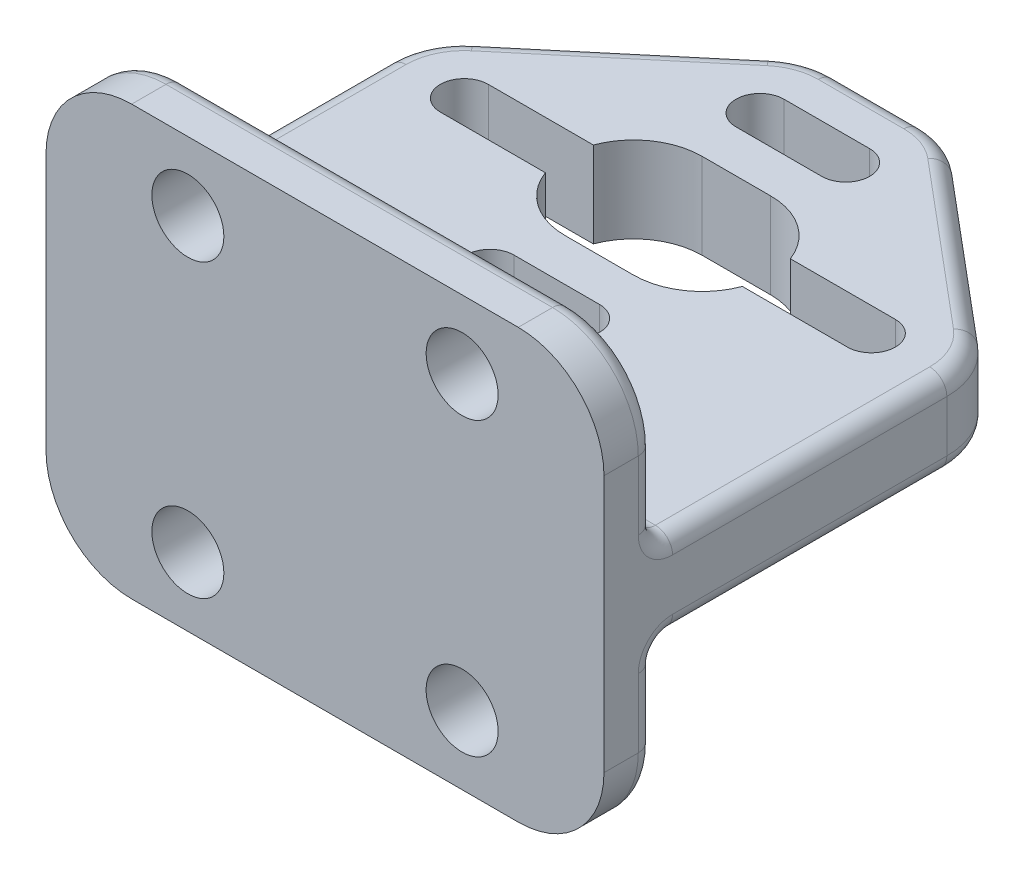
SolidWorks part; units mm, degrees
ref_plane "Front Plane" through (0, 0, 0) normal (0, 0, 1) x (1, 0, 0)
ref_plane "Top Plane" through (0, 0, 0) normal (0, 1, 0) x (1, 0, 0)
ref_plane "Right Plane" through (0, 0, 0) normal (1, 0, 0) x (0, 0, -1)
sketch "Sketch1" plane through (0, 0, 0) normal (0, 1, 0) x (1, 0, 0)
  line L0 (-9.375, 0) -> (9.375, 0) construction
  line L1 (0, -7.875) -> (0, 7.875) construction
  line L2 (-9.375, 1.4) -> (14.375, 1.4)
  line L3 (-9.375, -1.4) -> (14.375, -1.4)
  line L4 (0, 9.275) -> (5, 9.275)
  line L5 (5, 6.475) -> (0, 6.475)
  line L6 (0, -6.475) -> (5, -6.475)
  line L7 (5, -9.275) -> (0, -9.275)
  line L8 (0, 12.275) -> (5, 12.275)
  line L12 (5, -12.275) -> (0, -12.275)
  line L14 (-12.205, 3.3691) -> (-2.83, 11.2441)
  line L15 (7.83, 11.2441) -> (17.205, 3.3691)
  line L16 (7.83, -11.2441) -> (17.205, -3.3691)
  line L17 (-2.83, -11.2441) -> (-12.205, -3.3691)
  line L18 (-9.375, 4.4) -> (14.375, 4.4) construction
  line L19 (5, 3.475) -> (0, 3.475) construction
  line L20 (-9.375, -4.4) -> (14.375, -4.4) construction
  line L21 (0, -3.475) -> (5, -3.475) construction
  arc A0 (0, 9.275) -> (0, 6.475) centre (0, 7.875) ccw
  circle A1 centre (9.375, 0) radius 1.4 construction
  arc A2 (-9.375, 1.4) -> (-9.375, -1.4) centre (-9.375, 0) ccw
  arc A3 (0, -6.475) -> (0, -9.275) centre (0, -7.875) ccw
  arc A4 (14.375, -1.4) -> (14.375, 1.4) centre (14.375, 0) ccw
  arc A5 (5, 9.275) -> (5, 6.475) centre (5, 7.875) cw
  arc A6 (5, -6.475) -> (5, -9.275) centre (5, -7.875) cw
  arc A7 (5, 12.275) -> (7.83, 11.2441) centre (5, 7.875) cw
  arc A8 (0, 12.275) -> (-2.83, 11.2441) centre (0, 7.875) ccw
  arc A9 (17.205, -3.3691) -> (17.205, 3.3691) centre (14.375, 0) ccw
  arc A10 (-12.205, 3.3691) -> (-12.205, -3.3691) centre (-9.375, 0) ccw
  arc A12 (7.83, -11.2441) -> (5, -12.275) centre (5, -7.875) cw
  arc A13 (-9.375, 4.4) -> (-9.375, -4.4) centre (-9.375, 0) ccw construction
  arc A14 (5, 12.275) -> (5, 3.475) centre (5, 7.875) cw construction
  arc A15 (0, 12.275) -> (0, 3.475) centre (0, 7.875) ccw construction
  arc A16 (14.375, -4.4) -> (14.375, 4.4) centre (14.375, 0) ccw construction
  arc A17 (-2.83, -11.2441) -> (0, -12.275) centre (0, -7.875) ccw
  arc A18 (0, -3.475) -> (0, -12.275) centre (0, -7.875) ccw construction
  arc A19 (5, -3.475) -> (5, -12.275) centre (5, -7.875) cw construction
  point P4 (0, 0)
  point P8 (0, 0)
  dimension "D3" = 2.8
  dimension "D5" = 5
  dimension "D6" = 5
  dimension "D1" = 15.75
  dimension "D2" = 18.75
  dimension "D4" = 5
  dimension "D7" = 3
  dimension "D8" = 3
  dimension "D9" = 3
extrude "Boss-Extrude1" add sketch "Sketch1" along normal blind 5
sketch "Sketch2" plane through (0, 5, 0) normal (0, 1, 0) x (1, 0, 0)
  line L0 (14.375, 1.4) -> (-9.375, 1.4) construction
  line L1 (0.5, 4) -> (4.5, 4)
  line L2 (4.5, -4) -> (0.5, -4)
  circle A0 centre (2.5, 0) radius 4 construction
  arc A1 (0.5, 4) -> (0.5, -4) centre (0.5, 0) ccw
  arc A2 (4.5, -4) -> (4.5, 4) centre (4.5, 0) ccw
  point P6 (2.5, 1.4)
  dimension "D1" = 8
  dimension "D2" = 2
  dimension "D3" = 2
extrude "Cut-Extrude1" cut sketch "Sketch2" against normal through all
sketch "Sketch4" plane through (0, 5, 0) normal (0, 1, 0) x (1, 0, 0)
  line L0 (-13.775, 0) -> (-13.775, -20)
  line L1 (-13.775, -20) -> (18.775, -20)
  line L2 (18.775, -20) -> (18.775, 0)
  line L9 (-2.83, 11.2441) -> (-12.205, 3.3691)
  line L10 (-12.205, -3.3691) -> (-2.83, -11.2441)
  line L11 (0, -12.275) -> (5, -12.275)
  line L12 (7.83, -11.2441) -> (17.205, -3.3691)
  line L13 (17.205, 3.3691) -> (7.83, 11.2441)
  line L14 (5, 12.275) -> (0, 12.275)
  line L16 (-12.205, -3.3691) -> (-2.83, -11.2441)
  line L17 (0, -12.275) -> (5, -12.275)
  line L18 (7.83, -11.2441) -> (17.205, -3.3691)
  arc A0 (-12.205, 3.3691) -> (-12.205, -3.3691) centre (-9.375, 0) ccw construction
  arc A1 (17.205, -3.3691) -> (17.205, 3.3691) centre (14.375, 0) ccw construction
  arc A8 (0, 12.275) -> (-2.83, 11.2441) centre (0, 7.875) ccw
  arc A9 (-12.205, 3.3691) -> (-12.205, -3.3691) centre (-9.375, 0) ccw
  arc A10 (-2.83, -11.2441) -> (0, -12.275) centre (0, -7.875) ccw
  arc A11 (5, -12.275) -> (7.83, -11.2441) centre (5, -7.875) ccw
  arc A12 (17.205, -3.3691) -> (17.205, 3.3691) centre (14.375, 0) ccw
  arc A13 (7.83, 11.2441) -> (5, 12.275) centre (5, 7.875) ccw
  arc A15 (-13.775, 0) -> (-12.205, -3.3691) centre (-9.375, 0) ccw
  arc A16 (-2.83, -11.2441) -> (0, -12.275) centre (0, -7.875) ccw
  arc A17 (5, -12.275) -> (7.83, -11.2441) centre (5, -7.875) ccw
  arc A18 (17.205, -3.3691) -> (18.775, 0) centre (14.375, 0) ccw
  dimension "D1" = 20
  dimension "D2" = 0
extrude "Boss-Extrude3" add sketch "Sketch4" against normal blind 5
sketch "Sketch5" plane through (0, 5, 0) normal (0, 1, 0) x (1, 0, 0)
  line L0 (18.775, -20) -> (18.775, 0) construction
  line L1 (-13.775, -20) -> (18.775, -20)
  line L2 (-13.775, -20) -> (-13.775, -17)
  line L3 (-13.775, -17) -> (18.775, -17)
  line L4 (18.775, -20) -> (18.775, -17)
  dimension "D1" = 3
extrude "Boss-Extrude4" add sketch "Sketch5" along normal blind 10 and the other way blind 15
sketch "Sketch6" plane through (0, 0, 17) normal (0, 0, -1) x (-1, 0, 0)
  line L1 (-2.5, 15) -> (-2.5, 12.6542) construction
  line L2 (-18.775, 15) -> (13.775, 15) construction
  line L3 (-18.775, 2.5) -> (-20.9117, 2.5) construction
  line L4 (-18.775, 0) -> (-18.775, 5) construction
  line L5 (-18.775, 5) -> (-18.775, 15) construction
  circle A0 centre (-10.5, 11) radius 2.1
  circle A1 centre (5.5, 11) radius 2.1
  circle A2 centre (5.5, -6) radius 2.1
  circle A3 centre (-10.5, -6) radius 2.1
  point P23 (-18.775, 10)
  dimension "D1" = 4.2
  dimension "D2" = 8
  dimension "D3" = 1
extrude "Cut-Extrude2" cut sketch "Sketch6" against normal blind 10
fillet "Fillet1" radius 5 4 edges at (18.775, -10, 18.5) (18.775, 15, 18.5) (-13.775, -10, 18.5) (-13.775, 15, 18.5)
fillet "Fillet2" radius 1 30 edges at (2.5, 5, -12.275) (6.506, 5, -12.0093) (-1.506, 5, -12.0093) (2.5, -10, 17) (12.5175, 5, -7.3066) (-7.5175, 5, -7.3066) (17.3105, -8.5355, 17) (-12.3105, -8.5355, 17) (18.3632, 5, -1.8585) (-13.3632, 5, -1.8585) (18.775, -2.5, 17) (-13.775, -2.5, 17) (18.775, 0, 8.5) (18.775, 5, 8.5) (-13.775, 5, 8.5) (-13.775, 0, 8.5) (18.3632, 0, -1.8585) (12.5175, 0, -7.3066) (6.506, 0, -12.0093) (2.5, 0, -12.275) (-1.506, 0, -12.0093) (-13.3632, 0, -1.8585) (18.775, 7.5, 17) (17.3105, 13.5355, 17) (-13.775, 7.5, 17) (-12.3105, 13.5355, 17) (-7.5175, 0, -7.3066) (2.5, 15, 17) (2.5, 0, 17) (2.5, 5, 17)
